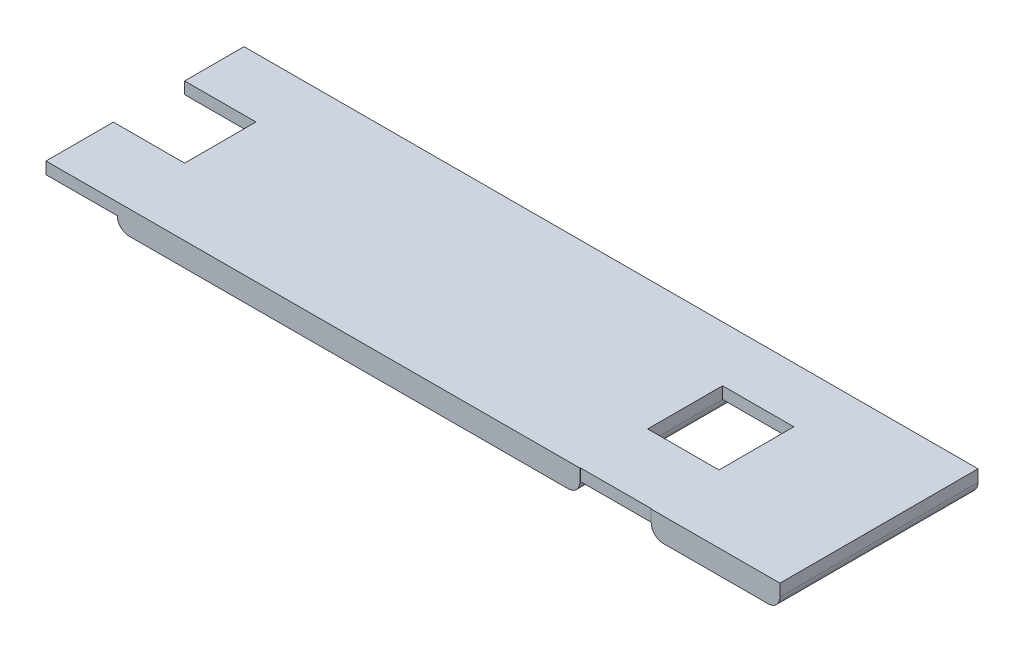
SolidWorks part; units mm, degrees
material "ABS"
ref_plane "X-Y Datum" through (0, 0, 0) normal (0, 0, 1) x (1, 0, 0)
ref_plane "X-Z Datum" through (0, 0, 0) normal (0, 1, 0) x (1, 0, 0)
ref_plane "Y-Z Datum" through (0, 0, 0) normal (1, 0, 0) x (0, 0, -1)
sketch "Sketch6" plane through (0, 0, -2000) normal (0, 0, 1) x (1, 0, 0)
  line L0 (-25.5275, 344.1696) -> (-25.5331, 347.1696) construction
  line L1 (-139.3165, 340.9552) -> (-28.5218, 341.164) construction
  line L2 (-25.5331, 347.1696) -> (-142.3278, 346.9495) construction
  line L3 (-142.3278, 346.9495) -> (-142.3222, 343.9495) construction
  line L4 (24.9668, 344.2591) -> (24.9668, 347.2648)
  line L5 (24.9668, 347.2648) -> (-7.5332, 347.2035)
  line L6 (-7.5332, 347.2035) -> (-7.5275, 344.2035)
  line L7 (-4.5219, 341.2092) -> (21.9724, 341.2591)
  line L8 (24.9668, 344.2591) -> (24.9668, 347.2648)
  line L9 (24.9668, 347.2648) -> (-7.5332, 347.2035)
  line L10 (-7.5332, 347.2035) -> (-7.5275, 344.2035)
  line L11 (-4.5219, 341.2092) -> (21.9724, 341.2591)
  line L12 (-25.5275, 344.1696) -> (-25.5331, 347.1696)
  line L13 (-139.3165, 340.9552) -> (-28.5218, 341.164)
  line L14 (-25.5331, 347.1696) -> (-142.3278, 346.9495)
  line L15 (-142.3278, 346.9495) -> (-142.3222, 343.9495)
  arc A0 (-28.5218, 341.164) -> (-25.5275, 344.1696) centre (-28.5275, 344.164) ccw construction
  arc A1 (-142.3222, 343.9495) -> (-139.3165, 340.9552) centre (-139.3222, 343.9552) ccw construction
  arc A2 (-7.5275, 344.2035) -> (-4.5219, 341.2092) centre (-4.5275, 344.2092) ccw
  arc A3 (21.9724, 341.2591) -> (24.9668, 344.2591) centre (21.9668, 344.2591) ccw
  arc A4 (-7.5275, 344.2035) -> (-4.5219, 341.2092) centre (-4.5275, 344.2092) ccw
  arc A5 (21.9724, 341.2591) -> (24.9668, 344.2591) centre (21.9668, 344.2591) ccw
  arc A6 (-28.5218, 341.164) -> (-25.5275, 344.1696) centre (-28.5275, 344.164) ccw
  arc A7 (-142.3222, 343.9495) -> (-139.3165, 340.9552) centre (-139.3222, 343.9552) ccw
  dimension "D1" = 0
extrude "Boss-Extrude4" add sketch "Sketch6" along normal blind 50
sketch "Sketch7" plane through (-6.8788, -0.013, 0) normal (-1, -0.0019, 0) x (0, 0, 1)
  line L0 (-1950, 344.2171) -> (-2000, 344.2171) construction
  line L1 (-1950.113, 347.3004) -> (-1967.113, 347.3004)
  line L2 (-1950.113, 347.3004) -> (-1950.113, 344.2171)
  line L3 (-1950.113, 344.2171) -> (-1967.113, 344.2171)
  line L4 (-1967.113, 347.3004) -> (-1967.113, 344.2171)
  line L5 (-2000, 347.2171) -> (-2000, 344.2171) construction
  line L7 (-2000, 344.2171) -> (-1986, 344.2171)
  line L8 (-2000, 344.2171) -> (-2000, 347.3004)
  line L9 (-2000, 347.3004) -> (-1986, 347.3004)
  line L10 (-1986, 344.2171) -> (-1986, 347.3004)
  line M3 (-2000, 347.2171) -> (-2000, 344.2171)
  line M4 (-2000, 344.2171) -> (-1950, 344.2171)
  line M6 (-1950, 347.2171) -> (-2000, 347.2171)
  dimension "D1" = 3.0833
  dimension "D2" = 17
  dimension "D3" = 49.887
  dimension "D4" = 14
  dimension "D5" = 3.0833
extrude "Boss-Extrude5" add sketch "Sketch7" along direction (1, 0.0019, 0) on the side of the normal up to surface (18 mm away) contours L4 L2 M6 M4 | L10 M4 M6 M3
sketch "Sketch8" plane through (-141.6735, -0.267, 0) normal (-1, -0.0019, 0) x (0, 0, 1)
  line L0 (-1950, 344.2171) -> (-2000, 344.2171) construction
  line L1 (-1950, 347.2171) -> (-1967, 347.2171)
  line L2 (-1950, 347.2171) -> (-1950, 344.2171)
  line L3 (-1950, 344.2171) -> (-1967, 344.2171)
  line L4 (-1967, 347.2171) -> (-1967, 344.2171)
  line L6 (-2000, 344.2171) -> (-1985, 344.2171)
  line L7 (-2000, 344.2171) -> (-2000, 347.2171)
  line L8 (-2000, 347.2171) -> (-1985, 347.2171)
  line L9 (-1985, 344.2171) -> (-1985, 347.2171)
  dimension "D1" = 15
  dimension "D2" = 17
  dimension "D3" = 3
extrude "Boss-Extrude6" add sketch "Sketch8" along normal up to surface (18 mm away)
